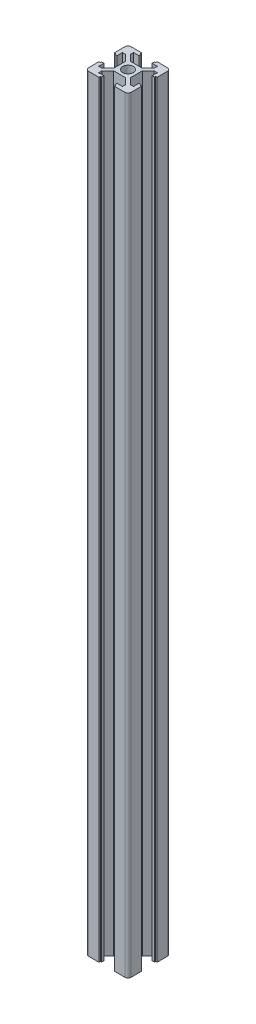
SolidWorks part; units mm, degrees
ref_plane "前视基准面" through (0, 0, 0) normal (0, 0, 1) x (1, 0, 0)
ref_plane "上视基准面" through (0, 0, 0) normal (0, 1, 0) x (1, 0, 0)
ref_plane "右视基准面" through (0, 0, 0) normal (1, 0, 0) x (0, 0, -1)
sketch "草图1" plane through (0, 0, 0) normal (0, 1, 0) x (1, 0, 0)
  line L0 (-10, 0) -> (10, 0) construction
  line L2 (10, 10) -> (3.65, 10)
  line L4 (-3.65, 10) -> (-3.65, 9.3033)
  line L5 (-3.65, 9.3033) -> (-3.1, 9.3033)
  line L6 (-3.1, 9.3033) -> (-3.1, 8.2)
  line L7 (-3.1, 8.2) -> (-5.6, 8.2)
  line L8 (-5.6, 8.2) -> (-5.6, 6.6607)
  line L9 (-5.6, 6.6607) -> (-2.8393, 3.9)
  line L11 (5.6, 6.6607) -> (5.6, 8.2)
  line L12 (5.6, 8.2) -> (3.1, 8.2)
  line L13 (3.1, 8.2) -> (3.1, 9.3033)
  line L14 (3.1, 9.3033) -> (3.65, 9.3033)
  line L15 (3.65, 9.3033) -> (3.65, 10)
  line L16 (-3.65, 10) -> (-10, 10)
  line L17 (0, 0) -> (0, 16.5896) construction
  line L18 (-2.8393, 3.9) -> (2.8393, 3.9)
  line L19 (2.8393, 3.9) -> (5.6, 6.6607)
  line L20 (10, -10) -> (10, -3.65)
  line L21 (10, 3.65) -> (9.3033, 3.65)
  line L22 (9.3033, 3.65) -> (9.3033, 3.1)
  line L23 (9.3033, 3.1) -> (8.2, 3.1)
  line L24 (8.2, 3.1) -> (8.2, 5.6)
  line L25 (8.2, 5.6) -> (6.6607, 5.6)
  line L26 (6.6607, 5.6) -> (3.9, 2.8393)
  line L27 (6.6607, -5.6) -> (8.2, -5.6)
  line L28 (8.2, -5.6) -> (8.2, -3.1)
  line L29 (8.2, -3.1) -> (9.3033, -3.1)
  line L30 (9.3033, -3.1) -> (9.3033, -3.65)
  line L31 (9.3033, -3.65) -> (10, -3.65)
  line L32 (10, 3.65) -> (10, 10)
  line L33 (3.9, 2.8393) -> (3.9, -2.8393)
  line L34 (3.9, -2.8393) -> (6.6607, -5.6)
  line L35 (0, 10) -> (0, -10) construction
  line L36 (0, 0) -> (16.5896, 0) construction
  line L37 (-10, -10) -> (-3.65, -10)
  line L38 (3.65, -10) -> (3.65, -9.3033)
  line L39 (3.65, -9.3033) -> (3.1, -9.3033)
  line L40 (3.1, -9.3033) -> (3.1, -8.2)
  line L41 (3.1, -8.2) -> (5.6, -8.2)
  line L42 (5.6, -8.2) -> (5.6, -6.6607)
  line L43 (5.6, -6.6607) -> (2.8393, -3.9)
  line L44 (-5.6, -6.6607) -> (-5.6, -8.2)
  line L45 (-5.6, -8.2) -> (-3.1, -8.2)
  line L46 (-3.1, -8.2) -> (-3.1, -9.3033)
  line L47 (-3.1, -9.3033) -> (-3.65, -9.3033)
  line L48 (-3.65, -9.3033) -> (-3.65, -10)
  line L49 (3.65, -10) -> (10, -10)
  line L50 (2.8393, -3.9) -> (-2.8393, -3.9)
  line L51 (-2.8393, -3.9) -> (-5.6, -6.6607)
  line L52 (10, 0) -> (-10, 0) construction
  line L53 (0, 0) -> (0, -16.5896) construction
  line L54 (-10, 10) -> (-10, 3.65)
  line L55 (-10, -3.65) -> (-9.3033, -3.65)
  line L56 (-9.3033, -3.65) -> (-9.3033, -3.1)
  line L57 (-9.3033, -3.1) -> (-8.2, -3.1)
  line L58 (-8.2, -3.1) -> (-8.2, -5.6)
  line L59 (-8.2, -5.6) -> (-6.6607, -5.6)
  line L60 (-6.6607, -5.6) -> (-3.9, -2.8393)
  line L61 (-6.6607, 5.6) -> (-8.2, 5.6)
  line L62 (-8.2, 5.6) -> (-8.2, 3.1)
  line L63 (-8.2, 3.1) -> (-9.3033, 3.1)
  line L64 (-9.3033, 3.1) -> (-9.3033, 3.65)
  line L65 (-9.3033, 3.65) -> (-10, 3.65)
  line L66 (-10, -3.65) -> (-10, -10)
  line L67 (-3.9, -2.8393) -> (-3.9, 2.8393)
  line L68 (-3.9, 2.8393) -> (-6.6607, 5.6)
  line L69 (0, -10) -> (0, 10) construction
  line L70 (0, 0) -> (-16.5896, 0) construction
  circle A0 centre (0, 0) radius 2.5
  point P12 (0, 3.9)
  dimension "D8" = 1.5
  dimension "D10" = 5
  dimension "D1" = 20
  dimension "D2" = 10
  dimension "D3" = 7.3
  dimension "D4" = 6.2
  dimension "D5" = 1.8
  dimension "D6" = 4.3
  dimension "D7" = 11.2
  dimension "D9" = 4
extrude "凸台-拉伸1" add sketch "草图1" along normal blind 360
fillet "圆角1" radius 1.5 4 edges at (-10, 180, 10) (-10, 180, -10) (10, 180, 10) (10, 180, -10)
